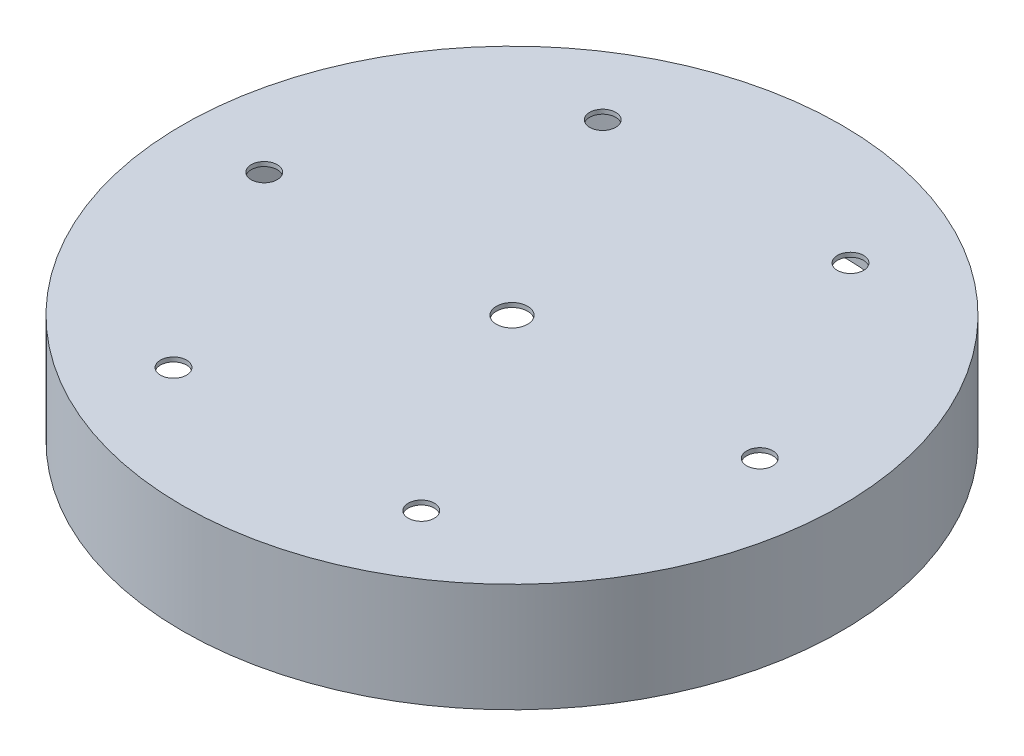
SolidWorks part; units mm, degrees
ref_plane "Front Plane" through (0, 0, 0) normal (0, 0, 1) x (1, 0, 0)
ref_plane "Top Plane" through (0, 0, 0) normal (0, 1, 0) x (1, 0, 0)
ref_plane "Right Plane" through (0, 0, 0) normal (1, 0, 0) x (0, 0, -1)
sketch "Sketch1" plane through (0, 0, 0) normal (0, 1, 0) x (1, 0, 0)
  circle A0 centre (0, 0) radius 96.266
  dimension "D1" = 192.532
extrude "Boss-Extrude1" add sketch "Sketch1" along normal blind 31.75 contours A0
sketch "Sketch2" plane through (0, 0, 0) normal (0, -1, 0) x (1, 0, 0)
  circle A4 centre (0, 0) radius 94.996
  circle A5 centre (0, 0) radius 94.996
  dimension "D1" = 1.27
extrude "Cut-Extrude1" cut sketch "Sketch2" against normal blind 30.48 contours A5
hole_wizard "23/64 (0.35938) Diameter Hole1" positions "3DSketch3" profile "Sketch4" hole size "23/64" standard "ANSI Inch" end condition through all
sketch3d "3DSketch3"
  point P0 (0, 0, 0)
  point P3 (0, 0, 0)
  point P5 (0, 0, 0)
  point P7 (0, 31.75, 0)
sketch "Sketch4" plane through (0, 31.75, 0) normal (1, 0, 0) x (0, 0, 1)
  line L0 (0, 0) -> (0, 31.75)
  line L1 (0, 31.75) -> (4.5641, 31.75)
  line L2 (4.5641, 31.75) -> (4.5641, 0)
  line L5 (4.5641, 0) -> (0, 0)
  line L11 (0, -6.35) -> (0, 107.95) construction
  dimension "Thru Hole Dia." = 9.1283
  dimension "Thru Hole Depth" = 31.75
sketch "Sketch5" plane through (0, 31.75, 0) normal (0, 1, 0) x (1, 0, 0)
  line L0 (-4.5641, 0) -> (-68.5721, 0)
  circle A0 centre (0, 0) radius 4.5641 construction
  circle A1 centre (-72.3821, 0) radius 3.81
  circle A2 centre (-36.1911, 62.6848) radius 3.81
  circle A3 centre (36.1911, 62.6848) radius 3.81
  circle A4 centre (72.3821, 0) radius 3.81
  circle A5 centre (36.1911, -62.6848) radius 3.81
  circle A6 centre (-36.1911, -62.6848) radius 3.81
  point P8 (0, 0)
  point P21 (0, 0)
  dimension "D2" = 72.3821
  dimension "D1" = 64.008
  dimension "D3" = 6
extrude "Cut-Extrude2" cut sketch "Sketch5" against normal blind 22.86 contours A4 | A3 | A2 | A1 | A6 | A5
